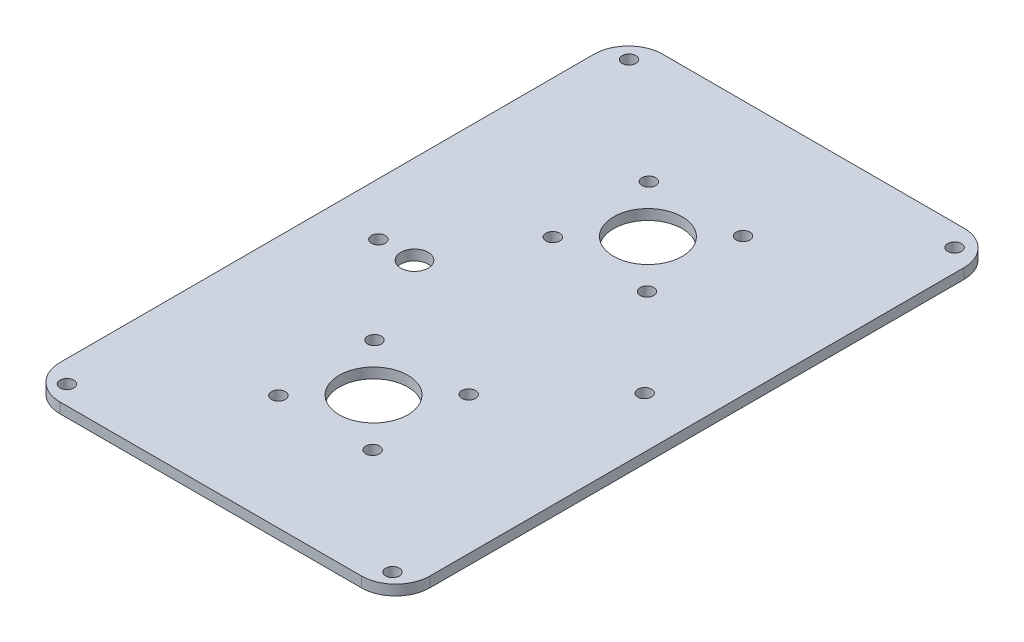
SolidWorks part; units mm, degrees
material "1060 合金"
ref_plane "前视基准面" through (0, 0, 0) normal (0, 0, 1) x (1, 0, 0)
ref_plane "上视基准面" through (0, 0, 0) normal (0, 1, 0) x (1, 0, 0)
ref_plane "右视基准面" through (0, 0, 0) normal (1, 0, 0) x (0, 0, -1)
sketch "草图1" plane through (0, 0, 0) normal (0, 1, 0) x (1, 0, 0)
  line L0 (-646.7167, 0) -> (31689.1197, 0) construction
  line L1 (0, -646.7167) -> (0, 31689.1197) construction
  line L2 (25, -40) -> (25, 40)
  line L3 (-975, 40) -> (49025, 40) construction
  line L5 (-18.915, 88.1963) -> (68.915, 88.1963)
  line L6 (78.915, 78.1963) -> (78.915, -77.4637)
  line L7 (68.915, -87.4637) -> (-18.915, -87.4637)
  line L8 (68.915, 88.1963) -> (-28.915, 88.1963)
  line L9 (-28.915, -911.8037) -> (-28.915, 49088.1963) construction
  line L10 (25, -960.7326) -> (25, 49039.2674) construction
  line L11 (-28.915, 78.1963) -> (-28.915, -77.4637)
  line L12 (-967.0296, 54) -> (49032.9704, 54) construction
  line L15 (11, -960) -> (11, 49040) construction
  arc A1 (68.915, -87.4637) -> (78.915, -77.4637) centre (68.915, -77.4637) ccw
  arc A2 (78.915, 78.1963) -> (68.915, 88.1963) centre (68.915, 78.1963) ccw
  circle A4 centre (72.465, 81.9363) radius 2
  circle A5 centre (72.465, -81.9363) radius 2
  circle A6 centre (-22.465, -81.9363) radius 2
  circle A7 centre (-22.465, 81.9363) radius 2
  arc A10 (-18.915, -87.4637) -> (-28.915, -77.4637) centre (-18.915, -77.4637) cw
  arc A11 (-28.915, 78.1963) -> (-18.915, 88.1963) centre (-18.915, 78.1963) cw
  circle A12 centre (25, 40) radius 10
  circle A13 centre (11.267, 54) radius 0.267
  circle A14 centre (11.267, 54) radius 2
  circle A15 centre (38.733, 54) radius 2
  circle A16 centre (38.733, 26) radius 2
  circle A17 centre (11.267, 26) radius 2
  circle A18 centre (11.267, -26) radius 2
  circle A19 centre (11.267, -54) radius 2
  circle A20 centre (25, -40) radius 10
  circle A21 centre (38.733, -26) radius 2
  circle A22 centre (38.733, -54) radius 2
  circle A23 centre (64.0517, -0.0062) radius 2
  circle A24 centre (-3.0648, -0.0062) radius 4
  circle A25 centre (-13.6009, -0.0062) radius 2
  point P4 (25, 0)
  point P8 (0, 0)
  point P11 (0, 0)
  point P13 (-28.915, -87.4637)
  point P14 (-78.915, 0)
  point P24 (25, 40)
  point P43 (25, 0)
  dimension "D3" = 14
  dimension "D6" = 4
  dimension "D9" = 14
  dimension "D1" = 10
  dimension "D2" = 80
  dimension "D4" = 107.83
  dimension "D5" = 53.915
  dimension "D7" = 6.26
  dimension "D8" = 6.45
extrude "凸台-拉伸1" add sketch "草图1" along normal blind 3 contours A11 L11 A10 L7 A1 L6 A2 L5 A5 A4 A6 A7
